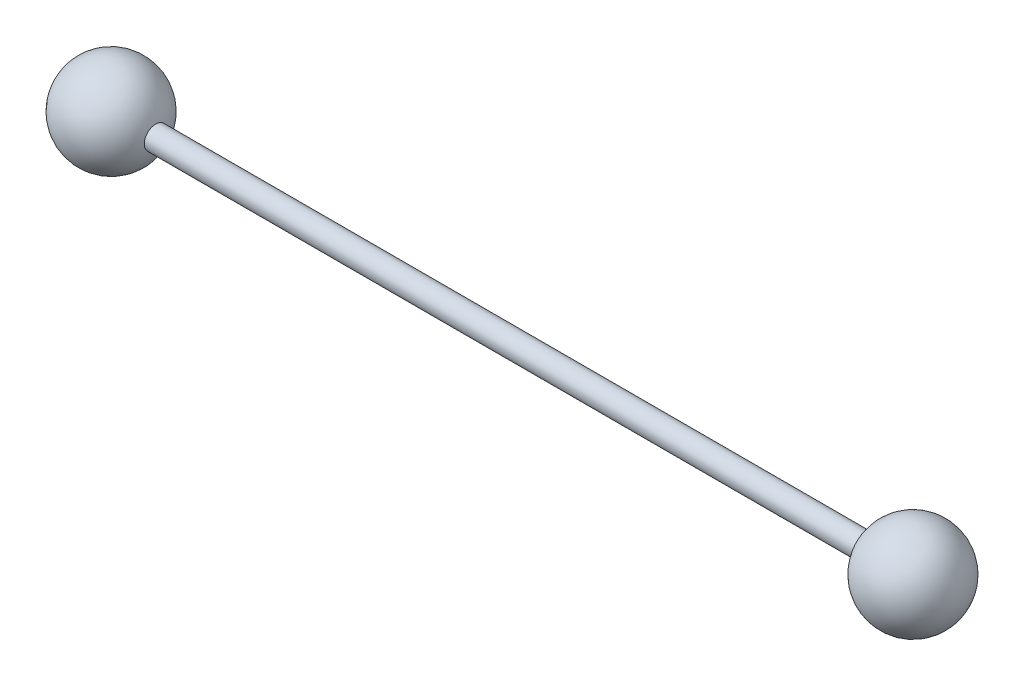
SolidWorks part; units mm, degrees
ref_plane "Front Plane" through (0, 0, 0) normal (0, 0, 1) x (1, 0, 0)
ref_plane "Top Plane" through (0, 0, 0) normal (0, 1, 0) x (1, 0, 0)
ref_plane "Right Plane" through (0, 0, 0) normal (1, 0, 0) x (0, 0, -1)
sketch "Sketch1" plane through (0, 0, 0) normal (1, 0, 0) x (0, 0, -1)
  circle A0 centre (0, 0) radius 1.27
  dimension "D1" = 2.54
extrude "Extrude1" add sketch "Sketch1" along normal mid plane 88.9
sketch "Sketch2" plane through (-44.45, 0, 0) normal (-1, 0, 0) x (0, 0, 1)
  line L0 (0, 8.7627) -> (0, -7.6077) construction
  line L1 (0, -5.1054) -> (0, 5.1054)
  arc A0 (0, 5.1054) -> (0, -5.1054) centre (0, 0) ccw
  dimension "D1" = 10.2108
revolve "Revolve1" add sketch "Sketch2" angle 360 about L0
sketch "Sketch3" plane through (44.45, 0, 0) normal (1, 0, 0) x (0, 0, -1)
  line L1 (0, 5.1054) -> (0, -5.1054)
  line L2 (0, 5.1054) -> (0, -5.1054)
  arc A1 (0, -5.1054) -> (0, 5.1054) centre (0, 0) ccw
  arc A2 (0, -5.1054) -> (0, 5.1054) centre (0, 0) ccw
  dimension "D1" = 0
revolve "Revolve2" add sketch "Sketch3" angle 360 about L2
